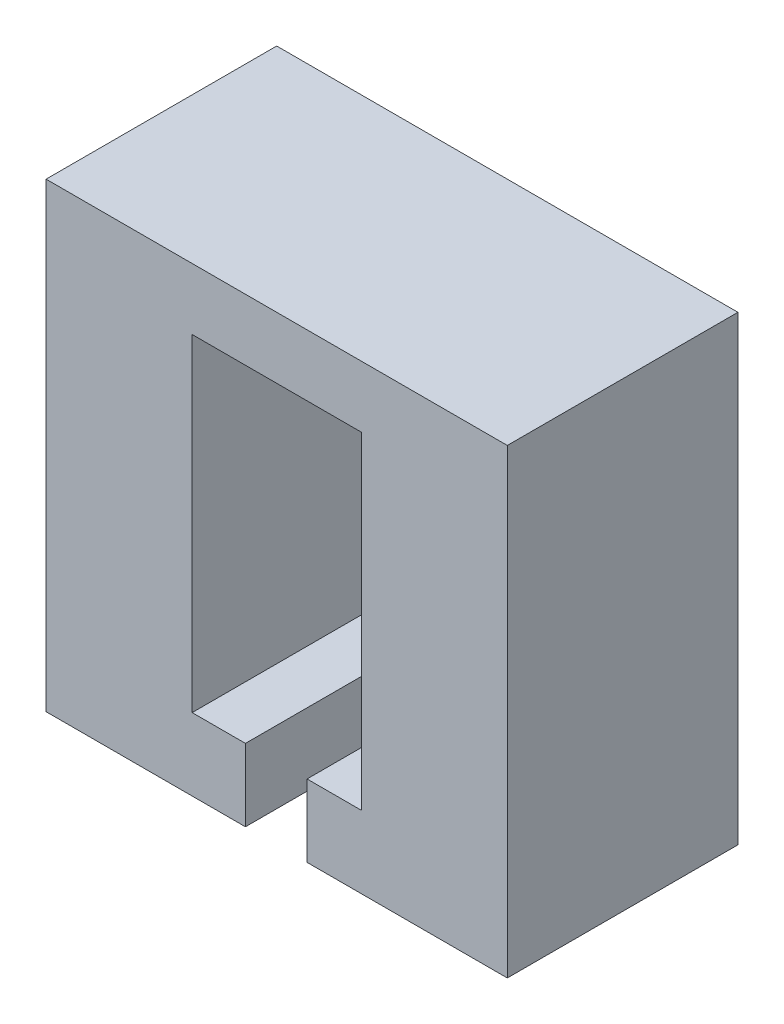
SolidWorks part; units mm, degrees
ref_plane "Front Plane" through (0, 0, 0) normal (0, 0, 1) x (1, 0, 0)
ref_plane "Top Plane" through (0, 0, 0) normal (0, 1, 0) x (1, 0, 0)
ref_plane "Right Plane" through (0, 0, 0) normal (1, 0, 0) x (0, 0, -1)
sketch "Sketch1" plane through (0, 0, 7.303) normal (0, 0, -1) x (-1, 0, 0)
  line L1 (-32.6747, -21.2507) -> (27.3253, -21.2507)
  line L2 (-32.6747, -21.2507) -> (-32.6747, 38.7493)
  line L3 (-32.6747, 38.7493) -> (27.3253, 38.7493)
  line L4 (27.3253, -21.2507) -> (27.3253, 38.7493)
  dimension "D1" = 60
  dimension "D2" = 60
extrude "Boss-Extrude1" add sketch "Sketch1" along normal blind 30
sketch "Sketch2" plane through (0, 0, -22.697) normal (0, 0, -1) x (-1, 0, 0)
  line L8 (8.3253, -11.8507) -> (8.3253, 30.7493)
  line L9 (8.3253, -11.8507) -> (-13.6747, -11.8507)
  line L11 (8.3253, 30.7493) -> (-13.6747, 30.7493)
  line L12 (-13.6747, -11.8507) -> (-13.6747, 30.7493)
  dimension "D6" = 42.6
extrude "Cut-Extrude1" cut sketch "Sketch2" against normal through all
sketch "Sketch4" plane through (0, 0, -22.697) normal (0, 0, -1) x (-1, 0, 0)
  line L0 (-13.6747, -11.8507) -> (8.3253, -11.8507) construction
  line L1 (1.3917, -11.8507) -> (-6.624, -11.8507)
  line L2 (1.3917, -11.8507) -> (1.3917, -21.2507)
  line L3 (1.3917, -21.2507) -> (-6.624, -21.2507)
  line L4 (-6.624, -11.8507) -> (-6.624, -21.2507)
  line L5 (-32.6747, -21.2507) -> (27.3253, -21.2507) construction
extrude "Cut-Extrude3" cut sketch "Sketch4" against normal through all
